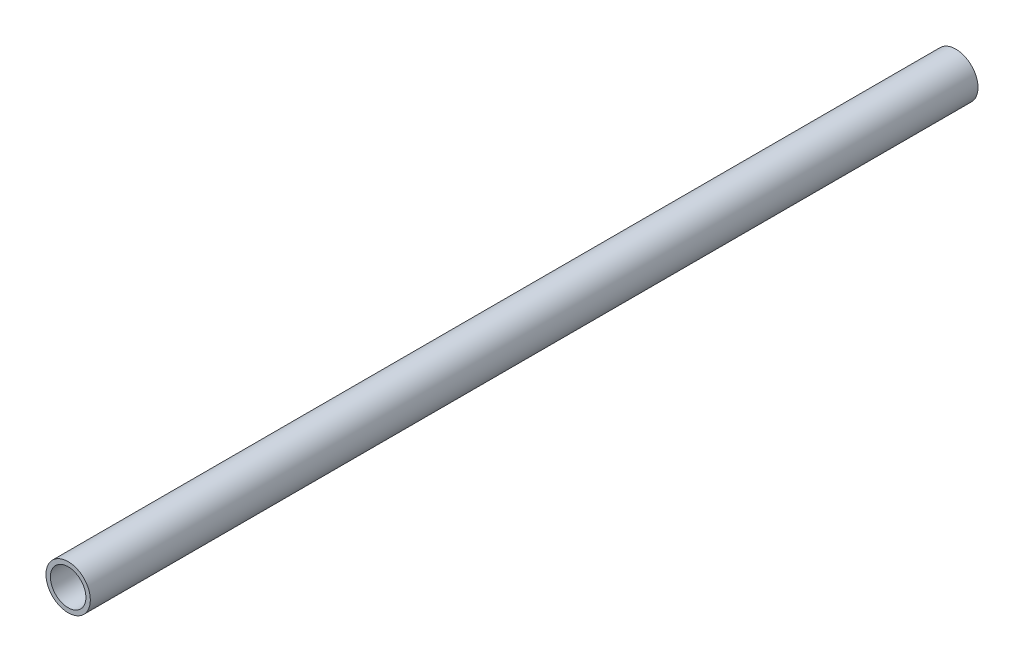
SolidWorks part; units mm, degrees
material "EM-CF"
ref_plane "Płaszczyzna przednia" through (0, 0, 0) normal (0, 0, 1) x (1, 0, 0)
ref_plane "Płaszczyzna górna" through (0, 0, 0) normal (0, 1, 0) x (1, 0, 0)
ref_plane "Płaszczyzna prawa" through (0, 0, 0) normal (1, 0, 0) x (0, 0, -1)
sketch "Szkic1" plane through (0, 0, 0) normal (0, 0, 1) x (1, 0, 0)
  circle A0 centre (0, 0) radius 4
  circle A1 centre (0, 0) radius 5
  dimension "D1" = 1
  dimension "D2" = 10
extrude "Dodanie-wyciągnięcie1" add sketch "Szkic1" along normal blind 200
